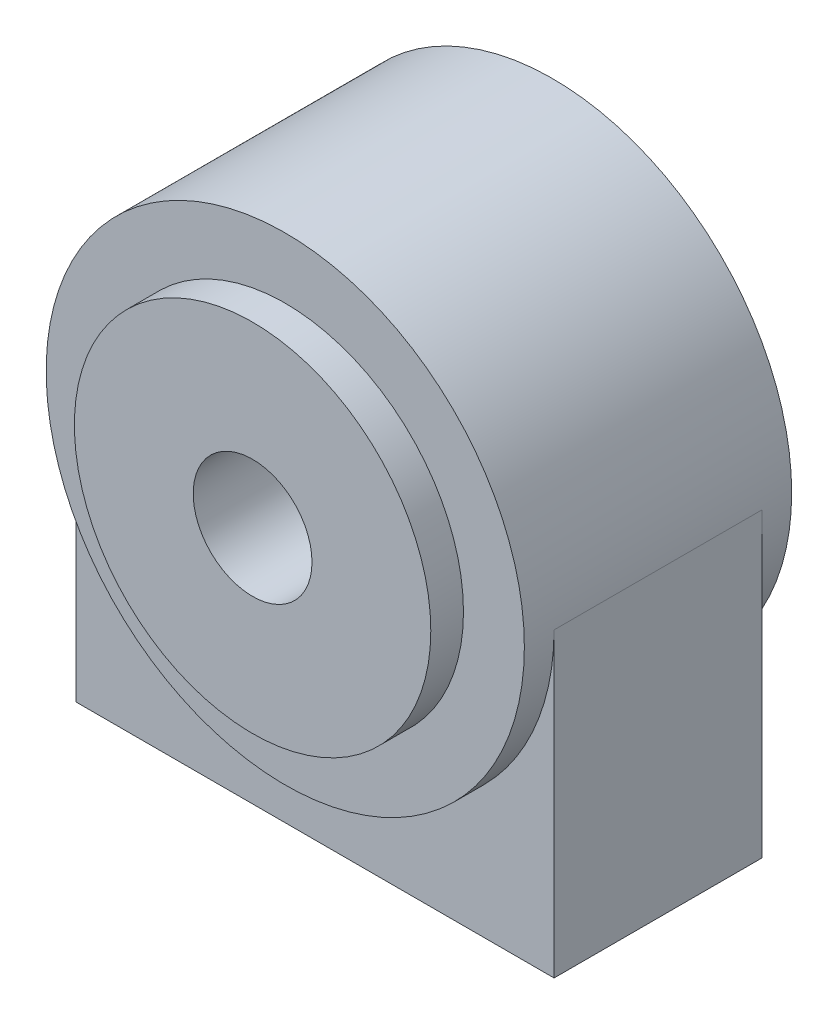
SolidWorks part; units mm, degrees
material "Plain Carbon Steel"
ref_plane "Front Plane" through (0, 0, 0) normal (0, 0, 1) x (1, 0, 0)
ref_plane "Top Plane" through (0, 0, 0) normal (0, 1, 0) x (1, 0, 0)
ref_plane "Right Plane" through (0, 0, 0) normal (1, 0, 0) x (0, 0, -1)
sketch "Sketch1" plane through (0, 0, 0) normal (0, 0, 1) x (1, 0, 0)
  line L0 (55, 0) -> (-55, 0) construction
  line L1 (-40.25, 0) -> (40.25, 0)
  line L2 (-40.25, 0) -> (-40.25, 50.75)
  line L3 (-40.25, 50.75) -> (40.25, 50.75)
  line L4 (40.25, 0) -> (40.25, 50.75)
  dimension "D1" = 50.75
  dimension "D2" = 80.5
extrude "Boss-Extrude1" add sketch "Sketch1" along normal mid plane 35
sketch "Sketch2" plane through (0, 0, 0) normal (0, 0, 1) x (1, 0, 0)
  line L0 (40.25, 50.75) -> (-40.25, 50.75) construction
  circle A0 centre (0, 50.75) radius 40.25
extrude "Boss-Extrude2" add sketch "Sketch2" along normal mid plane 45
sketch "Sketch3" plane through (0, 0, 0) normal (0, 0, 1) x (1, 0, 0)
  circle A0 centre (0, 50.75) radius 30
  dimension "D1" = 60
extrude "Boss-Extrude3" add sketch "Sketch3" along normal mid plane 56
sketch "Sketch4" plane through (0, 0, 0) normal (0, 0, 1) x (1, 0, 0)
  circle A0 centre (0, 50.75) radius 10
  dimension "D1" = 20
extrude "Cut-Extrude1" cut sketch "Sketch4" against normal through all both and the other way through all
